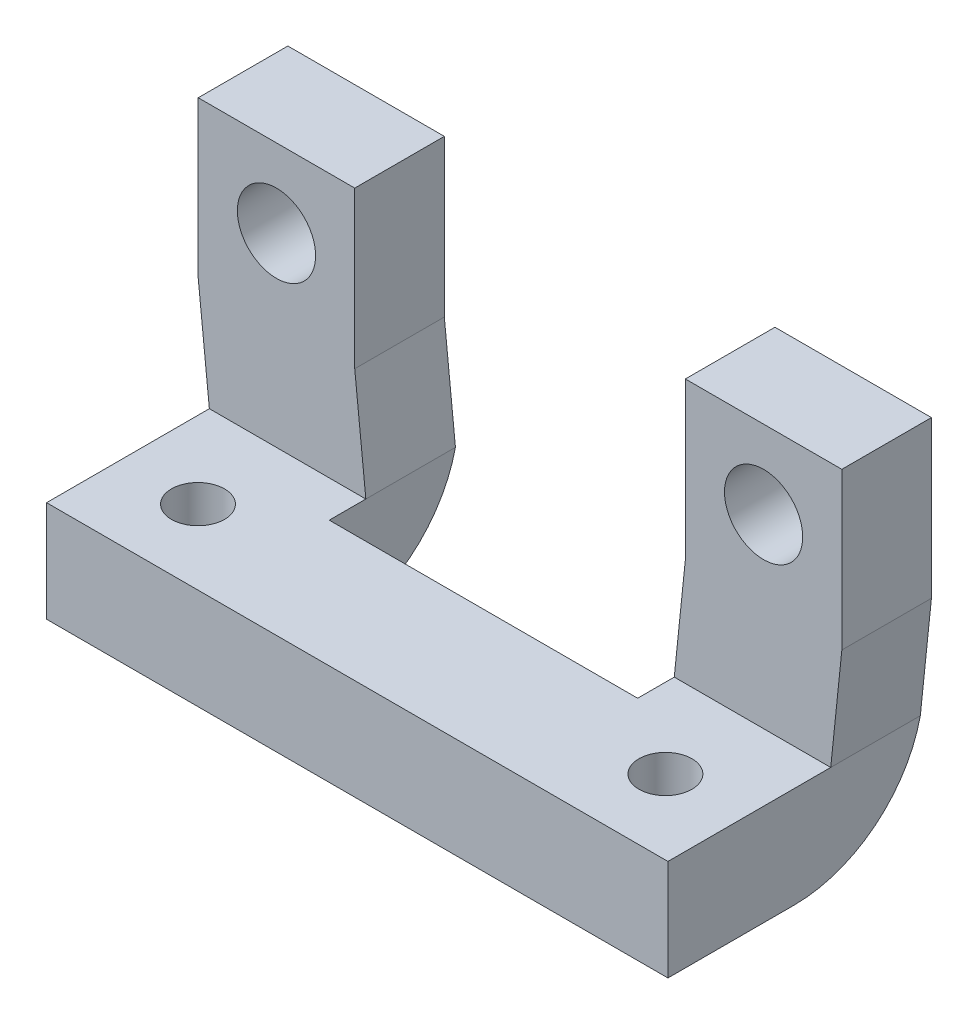
SolidWorks part; units mm, degrees
material "ABS"
ref_plane "Front Plane" through (0, 0, 0) normal (0, 0, 1) x (1, 0, 0)
ref_plane "Top Plane" through (0, 0, 0) normal (0, 1, 0) x (1, 0, 0)
ref_plane "Right Plane" through (0, 0, 0) normal (1, 0, 0) x (0, 0, -1)
sketch "Sketch1" plane through (0, 0, 0) normal (0, 1, 0) x (1, 0, 0)
  line L3 (12.31, 0) -> (12.31, 5)
  line L4 (12.31, 5) -> (-12.31, 5)
  line L5 (-12.31, 5) -> (-12.31, 0)
  line L8 (-9.26, 2.95) -> (9.26, 2.95) construction
  line L9 (-9.26, 4) -> (-9.26, 5) construction
  line L13 (-12.31, 0) -> (12.31, 0)
  line L17 (-10.31, 2.95) -> (-12.31, 2.95) construction
  line L18 (10.31, 2.95) -> (12.31, 2.95) construction
  circle A0 centre (-9.26, 2.95) radius 1.05
  circle A2 centre (9.26, 2.95) radius 1.05
  point P2 (6.0607, 0)
  point P4 (12.1293, 0)
  point P11 (0, 2.95)
  dimension "D2" = 2.1
  dimension "D1" = 18.52
  dimension "D3" = 5
  dimension "D4" = 1
  dimension "D6" = 2
  dimension "D7" = 2
extrude "Boss-Extrude1" add sketch "Sketch1" along normal blind 4
sketch "Sketch2" plane through (0, 0, -5) normal (0, 0, -1) x (-1, 0, 0)
  line L0 (-12.31, 4) -> (-12.75, 8.25)
  line L1 (-12.31, 4) -> (12.31, 4) construction
  line L2 (-12.75, 8.25) -> (-12.75, 14.45)
  line L3 (-12.75, 14.45) -> (-6.55, 14.45)
  line L4 (-6.55, 14.45) -> (-6.55, 8.25)
  line L5 (-6.55, 8.25) -> (-6.11, 4)
  line L7 (6.11, 4) -> (6.55, 8.25)
  line L8 (6.55, 8.25) -> (6.55, 14.45)
  line L9 (6.55, 14.45) -> (12.75, 14.45)
  line L10 (12.75, 14.45) -> (12.75, 8.25)
  line L11 (12.75, 8.25) -> (12.31, 4)
  line L13 (-12.75, 11.35) -> (-9.65, 11.35) construction
  line L14 (-9.65, 11.35) -> (-6.55, 11.35) construction
  line L15 (-9.65, 11.35) -> (-9.65, 14.45) construction
  line L16 (6.55, 11.35) -> (9.65, 11.35) construction
  line L17 (9.65, 11.35) -> (12.75, 11.35) construction
  line L18 (9.65, 11.35) -> (9.65, 14.45) construction
  line L19 (-6.55, 14.45) -> (6.55, 14.45) construction
  line L20 (-6.11, 4) -> (6.11, 4) construction
  line L21 (-12.31, 0) -> (12.31, 0) construction
  line L28 (-12.31, 4) -> (-6.11, 4)
  line L29 (6.11, 4) -> (12.31, 4)
  line L30 (-12.31, 4) -> (-12.31, 0) construction
  circle A0 centre (-9.65, 11.35) radius 1.55
  circle A1 centre (9.65, 11.35) radius 1.55
  point P16 (-8.1, 11.35)
  point P22 (-9.65, 12.9)
  point P26 (0, 14.45)
  point P29 (0, 0)
  point P30 (0, 4)
  dimension "D2" = 3.1
  dimension "D1" = 19.3
  dimension "D3" = 7.35
sketch "Sketch3" plane through (12.31, 0, 0) normal (1, 0, 0) x (0, 0, -1)
  line L0 (5, 4) -> (9, 4) construction
  line L2 (5, 4) -> (5, 0) construction
extrude "Boss-Extrude2" add sketch "Sketch2" along normal blind 5 separate body
sketch "Sketch6" plane through (12.31, 0, 0) normal (1, 0, 0) x (0, 0, -1)
  line L0 (0, 0) -> (5, 0) construction
  line L1 (5, 0) -> (5, 4)
  line L2 (5, 4) -> (10, 4)
  arc A0 (5, 0) -> (10, 4) centre (5, 5.125) ccw
extrude "Boss-Extrude3" add sketch "Sketch6" against normal up to vertex (6.2 mm away) up to point (6.11, 4, -10)
sketch "Sketch7" plane through (-12.31, 0, 0) normal (-1, 0, 0) x (0, 0, 1)
  line L0 (-5, 4) -> (-5, 0) construction
  line L1 (-10, 4) -> (-5, 4) construction
  line L2 (-5, 4) -> (-5, 0)
  line L3 (-10, 4) -> (-5, 4)
  arc A0 (-10, 4) -> (-5, 0) centre (-5, 5.125) ccw construction
  arc A1 (-10, 4) -> (-5, 0) centre (-5, 5.125) ccw
extrude "Boss-Extrude4" add sketch "Sketch7" against normal up to vertex (6.2 mm away) up to point (-6.11, 4, -10)
sketch "Sketch5" plane through (12.75, 0, 0) normal (1, 0, 0) x (0, 0, -1)
  line L2 (5, 14.45) -> (5, 8.25) construction
  line L4 (10, 14.45) -> (5, 14.45) construction
  line L5 (5, 14.45) -> (6.45, 14.45)
  line L6 (1.9, 4) -> (4, 4) construction
  line L7 (5, 14.45) -> (5, 4)
  line L8 (5, 4) -> (6.45, 4)
  line L9 (2.95, 4) -> (6.45, 4) construction
  line L10 (5, 4) -> (9, 4) construction
  line L11 (6.45, 4) -> (6.45, 14.45)
  dimension "D2" = 3.5
extrude "Cut-Extrude1" cut sketch "Sketch5" against normal up to surface (25.5 mm away) up to face at (-12.75, 11.35, -7.5)
equation "\"FrontScrewSpacingOO\"=22.7"
equation "\"BackScrewSpacingOO\"= 32.86"
equation "\"FrontToBack\"= 23.7"
equation "\"D1@Sketch1\"=\"FrontScrewSpacingOO\"-4.18"
equation "\"ScrewHeadDiam\"= 4.18"
equation "\"CliffWidth\"=21"
equation "\"SensHoleSpacing\"=19.3"
equation "\"D1@Sketch2\"=\"SensHoleSpacing\""
equation "\"M3DiamWithClear\"=3.1"
equation "\"D2@Sketch2\"=\"M3DiamWithClear\""
equation "\"SensHeight\"= 10.7"
equation "\"D3@Sketch2\"=\"SensHeight\"/2 + 2"
